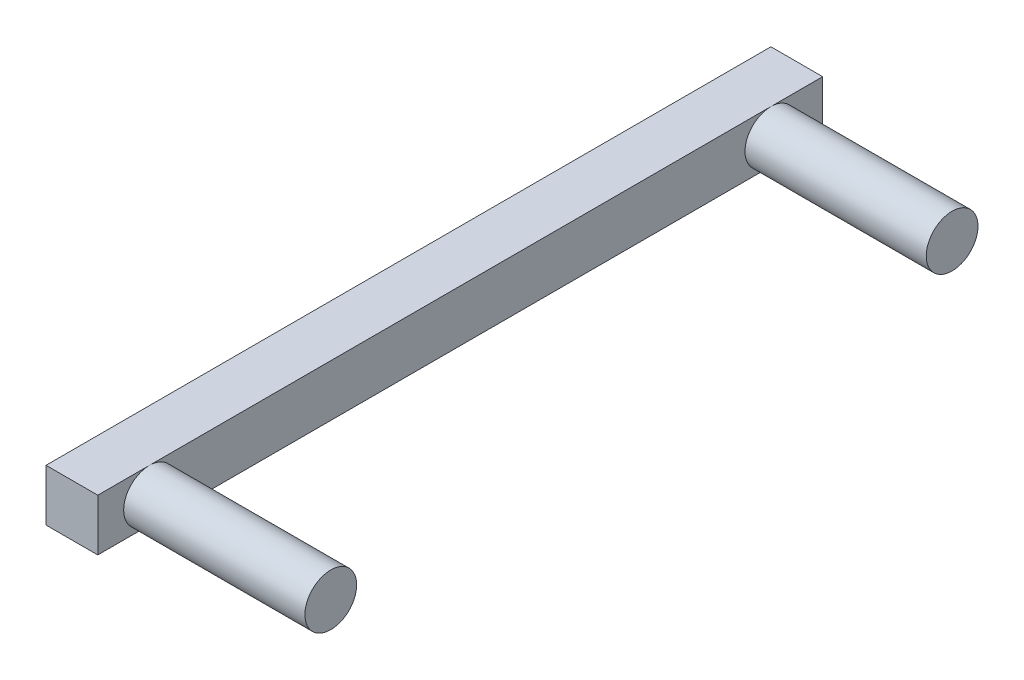
SolidWorks part; units mm, degrees
ref_plane "Спереди" through (0, 0, 0) normal (0, 0, 1) x (1, 0, 0)
ref_plane "Сверху" through (0, 0, 0) normal (0, 1, 0) x (1, 0, 0)
ref_plane "Справа" through (0, 0, 0) normal (1, 0, 0) x (0, 0, -1)
sketch "Эскиз1" plane through (0, 0, 0) normal (1, 0, 0) x (0, 0, -1)
  line L1 (0, 0) -> (140, 0)
  line L2 (0, 0) -> (0, 10)
  line L3 (0, 10) -> (140, 10)
  line L4 (140, 0) -> (140, 10)
  dimension "D1" = 10
  dimension "D2" = 140
extrude "Бобышка-Вытянуть1" add sketch "Эскиз1" along normal blind 10
sketch "Эскиз2" plane through (10, 0, 0) normal (1, 0, 0) x (0, 0, -1)
  line L0 (0, 5) -> (140, 5) construction
  line L1 (0, 10) -> (0, 0) construction
  line L2 (140, 0) -> (140, 10) construction
  circle A0 centre (10, 5) radius 5
  circle A1 centre (130, 5) radius 5
  dimension "D1" = 10
  dimension "D3" = 10
  dimension "D4" = 10
  dimension "D2" = 10
extrude "Бобышка-Вытянуть2" add sketch "Эскиз2" along normal blind 35
